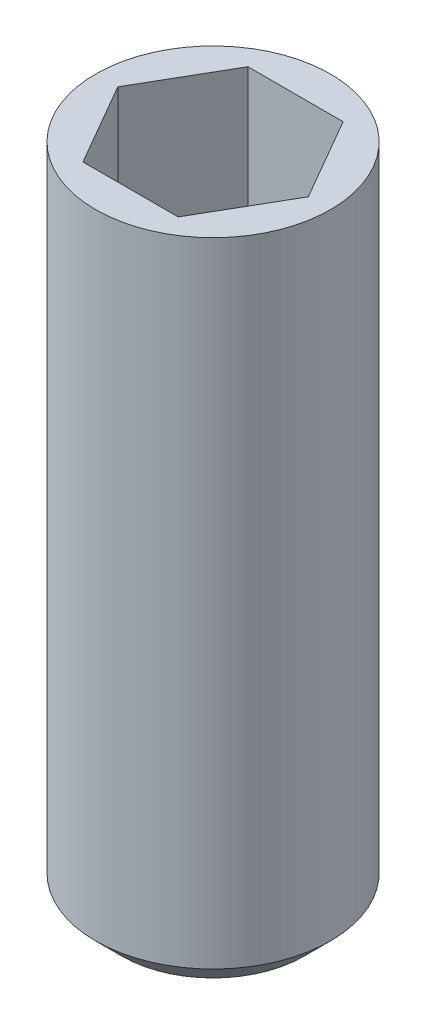
SolidWorks part; units mm, degrees
ref_plane "Front Plane" through (0, 0, 0) normal (0, 0, 1) x (1, 0, 0)
ref_plane "Top Plane" through (0, 0, 0) normal (0, 1, 0) x (1, 0, 0)
ref_plane "Right Plane" through (0, 0, 0) normal (1, 0, 0) x (0, 0, -1)
sketch "Sketch1" plane through (0, 0, 0) normal (0, 1, 0) x (1, 0, 0)
  circle A0 centre (0, 0) radius 1.1303
  dimension "D1" = 2.2606
extrude "Boss-Extrude1" add sketch "Sketch1" against normal blind 6.35
chamfer "Chamfer1" distance 0.254 angle 45 1 edges at (0, -6.35, 1.1303)
dome "Dome1" [suppressed] faces to dome 1 distance 0.508 parameters "D1"=0.508
sketch "Sketch2" plane through (0, 0, 0) normal (0, 1, 0) x (1, 0, 0)
  line L1 (-0.9165, 0) -> (-0.4583, -0.7937)
  line L2 (-0.4583, -0.7937) -> (0.4583, -0.7937)
  line L3 (0.4583, -0.7937) -> (0.9165, 0)
  line L4 (0.9165, 0) -> (0.4583, 0.7938)
  line L5 (0.4583, 0.7938) -> (-0.4583, 0.7938)
  line L6 (-0.4583, 0.7938) -> (-0.9165, 0)
  circle A0 centre (0, 0) radius 0.7937 construction
  dimension "D1" = 1.5875
extrude "Cut-Extrude1" cut sketch "Sketch2" against normal blind 1.27
